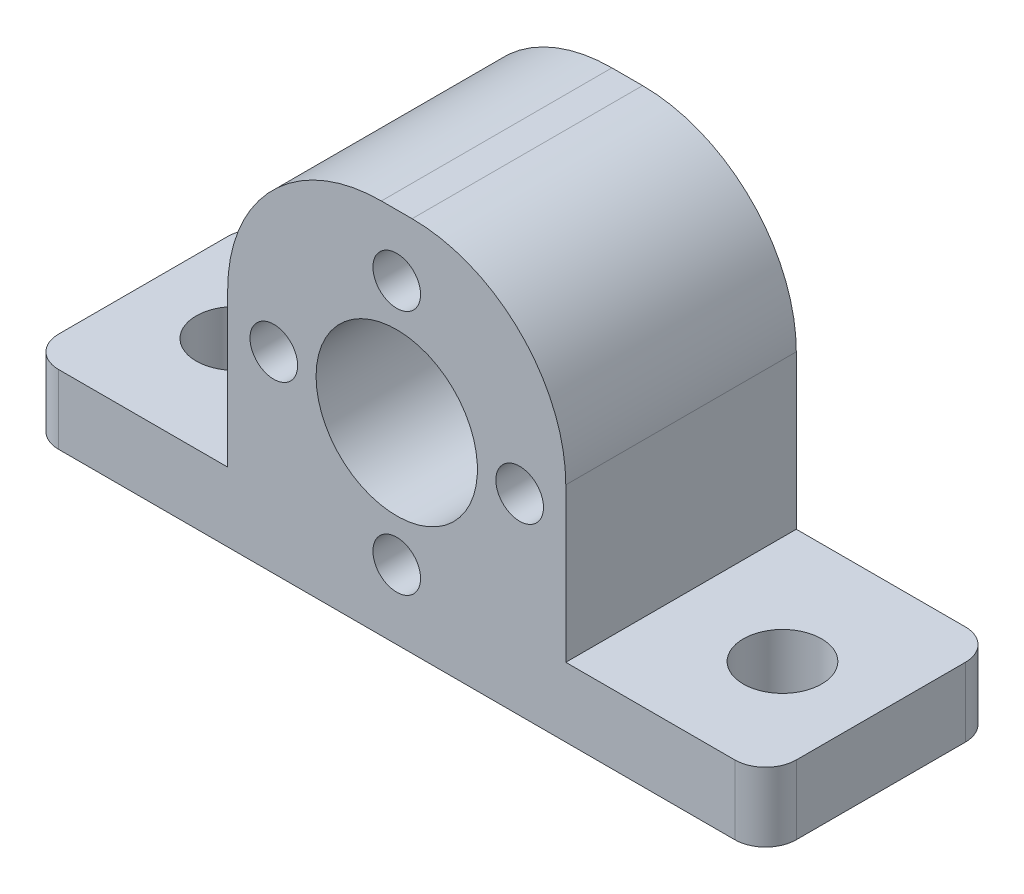
SolidWorks part; units mm, degrees
ref_plane "前视基准面" through (0, 0, 0) normal (0, 0, 1) x (1, 0, 0)
ref_plane "上视基准面" through (0, 0, 0) normal (0, 1, 0) x (1, 0, 0)
ref_plane "右视基准面" through (0, 0, 0) normal (1, 0, 0) x (0, 0, -1)
sketch "草图1" plane through (0, 0, 0) normal (0, 1, 0) x (1, 0, 0)
  line L1 (-25.9485, 7.8987) -> (22.0515, 7.8987)
  line L2 (-25.9485, 7.8987) -> (-25.9485, -7.1013)
  line L3 (-25.9485, -7.1013) -> (22.0515, -7.1013)
  line L4 (22.0515, 7.8987) -> (22.0515, -7.1013)
  dimension "D1" = 15
  dimension "D2" = 48
extrude "凸台-拉伸1" add sketch "草图1" along normal blind 4.5
sketch "草图2" plane through (0, 4.5, 0) normal (0, 1, 0) x (1, 0, 0)
  line L0 (22.0515, 7.8987) -> (-25.9485, 7.8987) construction
  line L1 (-12.9485, 7.8987) -> (9.0515, 7.8987)
  line L2 (-12.9485, 7.8987) -> (-12.9485, -7.1013)
  line L3 (-12.9485, -7.1013) -> (9.0515, -7.1013)
  line L4 (9.0515, 7.8987) -> (9.0515, -7.1013)
  line L5 (-25.9485, -7.1013) -> (22.0515, -7.1013) construction
  line L6 (22.0515, -7.1013) -> (22.0515, 7.8987) construction
  dimension "D1" = 22
  dimension "D2" = 13
extrude "凸台-拉伸2" add sketch "草图2" along normal blind 20
fillet "圆角1" radius 10 2 edges at (9.0515, 24.5, -0.3987) (-12.9485, 24.5, -0.3987)
sketch "草图3" plane through (0, 4.5, 0) normal (0, 1, 0) x (1, 0, 0)
  line L0 (-25.9485, 7.8987) -> (-25.9485, -7.1013) construction
  line L1 (22.0515, -7.1013) -> (22.0515, 7.8987) construction
  circle A0 centre (-19.9485, 0.3987) radius 2.55
  circle A1 centre (16.0515, 0) radius 2.55
  dimension "D1" = 5.1
  dimension "D2" = 6
  dimension "D3" = 6
  dimension "D4" = 5.1
extrude "切除-拉伸1" cut sketch "草图3" against normal through all
sketch "草图4" plane through (0, 0, -7.8987) normal (0, 0, -1) x (-1, 0, 0)
  line L0 (2.9485, 24.5) -> (0.9485, 24.5) construction
  line L2 (12.9485, 14.5) -> (12.9485, 4.5) construction
  circle A0 centre (1.9485, 12.5) radius 5.25
  circle A1 centre (1.9485, 12.5) radius 8 construction
  circle A2 centre (1.9485, 20.5) radius 1.55
  circle A3 centre (9.9485, 12.5) radius 1.55
  circle A4 centre (1.9485, 4.5) radius 1.55
  circle A5 centre (-6.0515, 12.5) radius 1.55
  dimension "D1" = 12
  dimension "D2" = 16
  dimension "D3" = 10.5
  dimension "D4" = 3.1
  dimension "D5" = 11
extrude "切除-拉伸2" cut sketch "草图4" against normal blind 20
fillet "圆角2" radius 2 4 edges at (22.0515, 2.25, -7.8987) (22.0515, 2.25, 7.1013) (-25.9485, 2.25, -7.8987) (-25.9485, 2.25, 7.1013)
